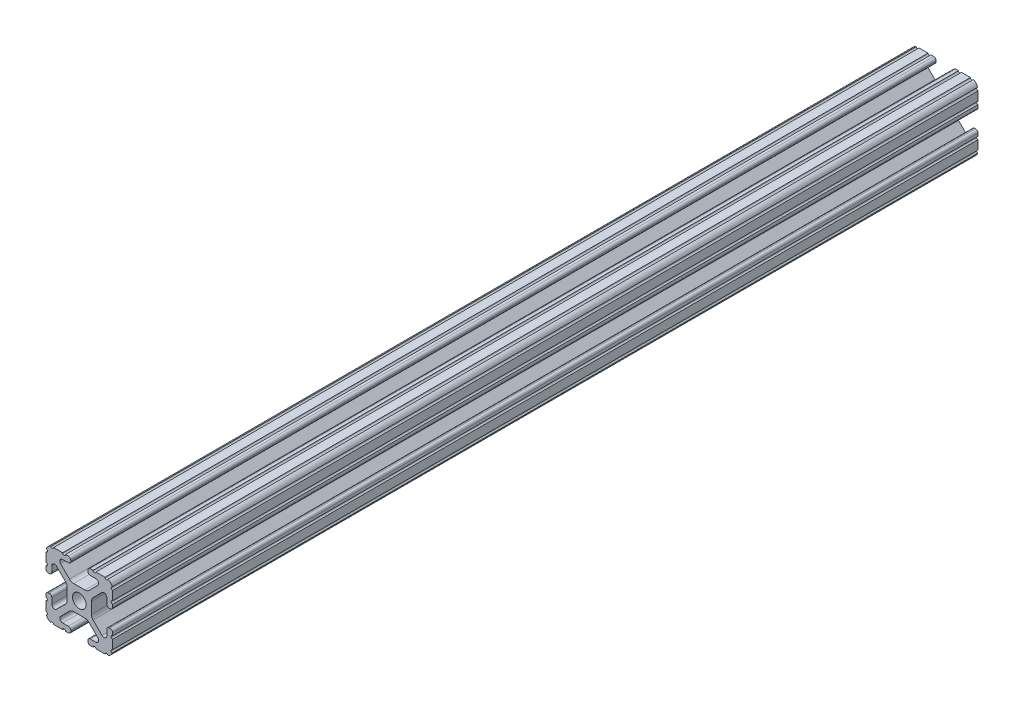
SolidWorks part; units mm, degrees
ref_plane "Front Plane" through (0, 0, 0) normal (0, 0, 1) x (1, 0, 0)
ref_plane "Top Plane" through (0, 0, 0) normal (0, 1, 0) x (1, 0, 0)
ref_plane "Right Plane" through (0, 0, 0) normal (1, 0, 0) x (0, 0, -1)
sketch "Sketch2" plane through (0, 0, 0) normal (0, 0, 1) x (1, 0, 0)
  line L0 (0, 12.7) -> (0, -12.7) construction
  line L1 (-12.7, 0) -> (12.7, 0) construction
  line L2 (3.2512, -12.7) -> (12.7, -12.7)
  line L3 (12.7, -12.7) -> (12.7, -3.2512)
  line L4 (3.2512, -12.7) -> (3.2512, -10.4902)
  line L5 (3.2512, -10.4902) -> (8.9276, -10.4902)
  line L6 (8.9276, -10.4902) -> (3.0856, -4.6482)
  line L7 (0, 0) -> (12.7, -12.7) construction
  line L8 (12.7, -3.2512) -> (10.4902, -3.2512)
  line L9 (10.4902, -3.2512) -> (10.4902, -8.9276)
  line L10 (10.4902, -8.9276) -> (4.6482, -3.0856)
  circle A0 centre (0, 0) radius 2.6035
  arc A1 (6.3485, -10.4902) -> (7.1039, -8.6665) centre (6.3485, -9.4219) ccw construction
  point P8 (0, -4.6482)
  dimension "Center Hole Diameter" = 5.207
  dimension "Rail Height" = 25.4
  dimension "Rail Width" = 25.4
  dimension "T-Slot Width" = 6.5024
  dimension "Slot Inner Width" = 14.8336
  dimension "Thickness" = 2.2098
  dimension "Slot Depth" = 5.842
  dimension "D1" = 2.2098
sketch "Sketch3" plane through (0, 0, 0) normal (1, 0, 0) x (0, 0, -1)
  line L0 (-165.1, -12.7) -> (165.1, -12.7) construction
  line L1 (-139.7, 0) -> (139.7, 0) construction
  dimension "Length" = 330.2
  dimension "D1" = 25.4
sketch "Sketch4" plane through (0, 0, 0) normal (0, 0, 1) x (1, 0, 0)
  line L0 (4.1904, -12.7) -> (10.1173, -12.7)
  line L1 (3.2512, -12.7) -> (12.7, -12.7) construction
  line L2 (3.2512, -12.7) -> (3.2512, -10.4902) construction
  line L3 (3.2512, -10.4902) -> (8.9276, -10.4902) construction
  line L4 (3.2512, -11.4294) -> (3.2512, -11.7608)
  line L5 (4.1904, -10.4902) -> (6.3485, -10.4902)
  line L6 (0, -4.6482) -> (2.164, -4.6482)
  line L7 (8.9276, -10.4902) -> (3.0856, -4.6482) construction
  line L8 (3.7373, -5.2999) -> (7.1039, -8.6665)
  line L9 (12.7, -12.7) -> (12.7, -3.2512) construction
  line L10 (10.4902, -8.9276) -> (4.6482, -3.0856) construction
  line L11 (10.4902, -3.2512) -> (10.4902, -8.9276) construction
  line L12 (10.4902, -6.3485) -> (10.4902, -4.1904)
  line L13 (12.7, -3.2512) -> (10.4902, -3.2512) construction
  line L14 (11.4294, -3.2512) -> (11.7608, -3.2512)
  line L15 (12.7, -4.1904) -> (12.7, -10.1173)
  line L16 (8.6665, -7.1039) -> (5.2999, -3.7373)
  line L17 (4.6482, 0) -> (4.6482, -2.164)
  line L18 (-12.7, 0) -> (12.7, 0) construction
  line L19 (0, -4.6482) -> (0, -2.6035)
  line L20 (0, 12.7) -> (0, -12.7) construction
  line L21 (4.6482, 0) -> (2.6035, 0)
  arc A0 (3.2512, -11.7608) -> (4.1904, -12.7) centre (4.1904, -11.7608) ccw
  arc A2 (3.2512, -11.4294) -> (4.1904, -10.4902) centre (4.1904, -11.4294) cw
  arc A3 (6.3485, -10.4902) -> (7.1039, -8.6665) centre (6.3485, -9.4219) ccw
  arc A4 (2.164, -4.6482) -> (3.7373, -5.2999) centre (2.164, -6.8732) cw
  arc A5 (10.1173, -12.7) -> (12.7, -10.1173) centre (10.1173, -10.1173) ccw
  arc A6 (8.6665, -7.1039) -> (10.4902, -6.3485) centre (9.4219, -6.3485) ccw
  arc A7 (10.4902, -4.1904) -> (11.4294, -3.2512) centre (11.4294, -4.1904) cw
  arc A8 (11.7608, -3.2512) -> (12.7, -4.1904) centre (11.7608, -4.1904) cw
  arc A9 (5.2999, -3.7373) -> (4.6482, -2.164) centre (6.8732, -2.164) cw
  circle A10 centre (0, 0) radius 2.6035 construction
  arc A11 (0, -2.6035) -> (2.6035, 0) centre (0, 0) ccw
  dimension "D1" = 2.5827
  dimension "D2" = 2.225
  dimension "D3" = 0.9392
extrude "Boss-Extrude1" add sketch "Sketch4" along normal mid plane 330.2
sketch "Sketch5" plane through (0, 0, 0) normal (0, 0, 1) x (1, 0, 0)
  line L0 (3.2512, -12.7) -> (12.7, -12.7) construction
  line L1 (4.1904, -10.4902) -> (6.3485, -10.4902) construction
  line L3 (0, 0) -> (12.7, -12.7) construction
  line L4 (6.3485, -10.4902) -> (6.3485, -12.7) construction
  line L5 (8.9276, -10.4902) -> (3.0856, -4.6482) construction
  circle A0 centre (10.3562, -12.7) radius 0.5524
  circle A1 centre (5.796, -12.7) radius 0.5524
  circle A2 centre (12.7, -10.3562) radius 0.5524
  circle A3 centre (12.7, -5.796) radius 0.5524
  point P10 (5.2694, -10.4902)
  point P12 (9.4219, -6.3485)
  dimension "D1" = 1.1049
extrude "Cut-Extrude1" cut sketch "Sketch5" against normal through all both and the other way through all
mirror "Mirror1" about plane through (0, 0, 0) normal (1, 0, 0) of bodies 137 134
mirror "Mirror2" about plane through (0, 0, 0) normal (0, 1, 0) of bodies 135
equation "\"D1@Boss-Extrude1\"=\"Length@Sketch3\""
equation "\"D1@Sketch2\"=\"Thickness@Sketch2\""
equation "\"D2@Sketch4\"=\"Slot Inner Width@Sketch2\"*0.15"
equation "\"D1@Sketch4\"=\"D3@Sketch4\"*2.75"
equation "\"D3@Sketch4\"=\"Thickness@Sketch2\"*0.425"
equation "\"D1@Sketch5\"=\"Thickness@Sketch2\"*0.5"
